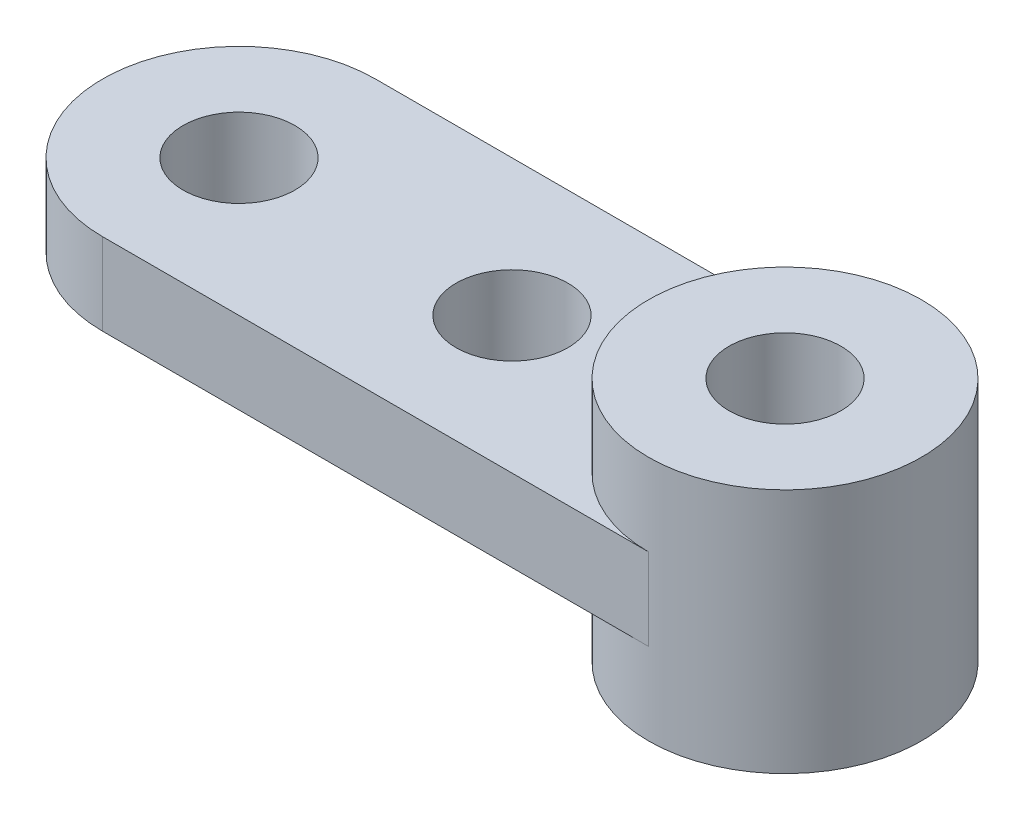
SolidWorks part; units mm, degrees
ref_plane "Front Plane" through (0, 0, 0) normal (0, 0, 1) x (1, 0, 0)
ref_plane "Top Plane" through (0, 0, 0) normal (0, 1, 0) x (1, 0, 0)
ref_plane "Right Plane" through (0, 0, 0) normal (1, 0, 0) x (0, 0, -1)
sketch "Sketch1" plane through (0, 0, 0) normal (0, 1, 0) x (1, 0, 0)
  line L0 (-10, -5) -> (-7.95, -5) construction
  line L1 (-10, 0) -> (-5, 0)
  line L2 (-10, -10) -> (-5, -10)
  line L3 (0, -33) -> (0, 33) construction
  line L4 (-5, 0) -> (5, 0)
  line L9 (5, 0) -> (10, 0)
  line L10 (0, 22.95) -> (0, 25) construction
  line L11 (-2.05, -5) -> (2.05, -5) construction
  line L12 (7.95, -5) -> (10, -5) construction
  line L14 (5, -10) -> (10, -10)
  line L15 (0, -7.05) -> (0, -2.95) construction
  line L16 (-5, -10) -> (5, -10)
  arc A0 (-10, 0) -> (-10, -10) centre (-10, -5) ccw
  arc A1 (10, -10) -> (10, 0) centre (10, -5) ccw
  circle A2 centre (10, -5) radius 2.05
  circle A3 centre (-10, -5) radius 2.05
  circle A4 centre (0, -5) radius 2.05
  point P2 (0, 0)
  point P17 (0, 0)
  point P18 (0, -5)
  dimension "D3" = 4.1
  dimension "D4" = 4.1
  dimension "D10" = 10
  dimension "D6" = 5
  dimension "D11" = 10
  dimension "D1" = 10
  dimension "D2" = 20
extrude "Boss-Extrude1" add sketch "Sketch1" along normal mid plane 3
sketch "Sketch2" plane through (0, 1.5, 0) normal (0, 1, 0) x (1, 0, 0)
  circle A0 centre (10, -5) radius 5
  circle A1 centre (10, -5) radius 2.05
extrude "Boss-Extrude2" add sketch "Sketch2" along normal blind 3
mirror "Mirror1" about plane through (0, 0, 0) normal (0, 1, 0) of "Boss-Extrude2"
